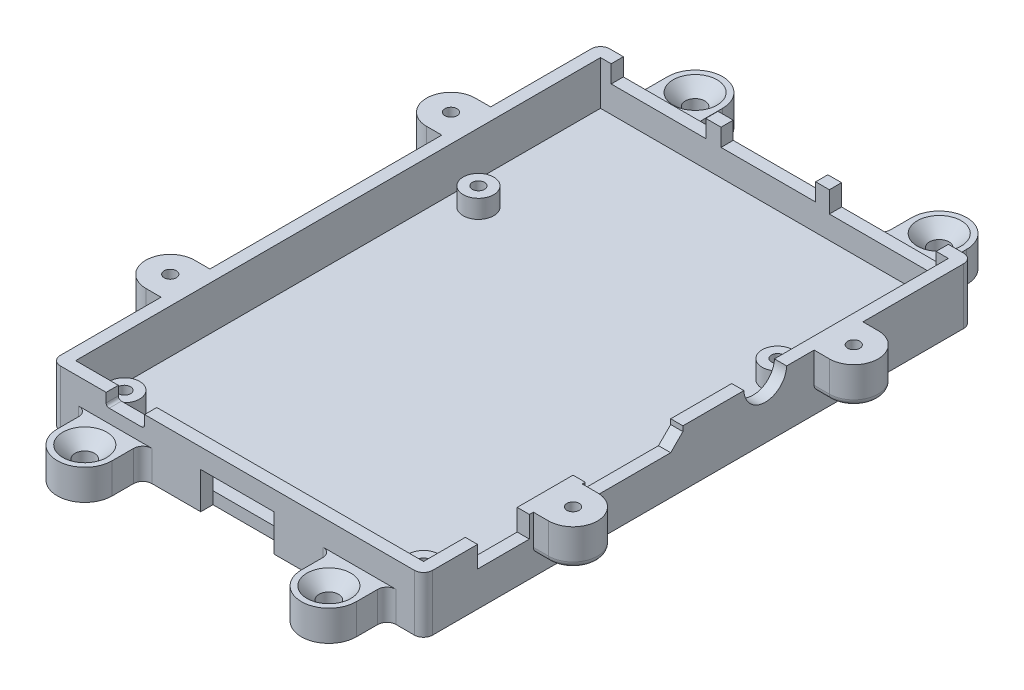
SolidWorks part; units mm, degrees
ref_plane "Спереди" through (0, 0, 0) normal (0, 0, 1) x (1, 0, 0)
ref_plane "Сверху" through (0, 0, 0) normal (0, 1, 0) x (1, 0, 0)
ref_plane "Справа" through (0, 0, 0) normal (1, 0, 0) x (0, 0, -1)
sketch "Эскиз1" plane through (0, 0, 0) normal (0, 1, 0) x (1, 0, 0)
  line L0 (0, 45) -> (0, -45) construction
  line L1 (-30.5, 45) -> (30.5, 45)
  line L2 (-30.5, 45) -> (-30.5, -45)
  line L3 (-30.5, -45) -> (30.5, -45)
  line L4 (30.5, 45) -> (30.5, -45)
  line L6 (-30.5, 0) -> (30.5, 0) construction
  point P8 (0, 0)
  dimension "D1" = 61
  dimension "D2" = 90
extrude "тело" add sketch "Эскиз1" along normal blind 9.2
sketch "Эскиз2" plane through (0, 9.2, 0) normal (0, 1, 0) x (1, 0, 0)
  line L0 (-28.5, -43) -> (28.5, 43) construction
  line L1 (-28.5, 43) -> (28.5, 43)
  line L2 (-28.5, 43) -> (-28.5, -43)
  line L3 (-28.5, -43) -> (28.5, -43)
  line L4 (28.5, 43) -> (28.5, -43)
  line L5 (0, 45) -> (0, -45) construction
  line L6 (30.5, 45) -> (-30.5, 45) construction
  line L7 (-30.5, -45) -> (30.5, -45) construction
  line L9 (-30.5, 45) -> (-30.5, -45) construction
  line L10 (-30.5, 0) -> (30.5, 0) construction
  line L11 (30.5, -45) -> (30.5, 45) construction
  point P16 (0, 0)
  dimension "D1" = 86
  dimension "D2" = 57
extrude "углубление под плату" cut sketch "Эскиз2" against normal blind 7.2
sketch "Эскиз3" plane through (0, 2, 0) normal (0, 1, 0) x (1, 0, 0)
  line L0 (0, 43) -> (0, -43) construction
  line L1 (-24.5, 19) -> (24.5, 19) construction
  line L2 (-24.5, 19) -> (-24.5, -39) construction
  line L3 (-24.5, -39) -> (24.5, -39) construction
  line L4 (24.5, 19) -> (24.5, -39) construction
  line L5 (28.5, 43) -> (-28.5, 43) construction
  line L6 (-28.5, -43) -> (28.5, -43) construction
  circle A0 centre (-24.5, 19) radius 2.5
  circle A1 centre (24.5, 19) radius 2.5
  circle A2 centre (24.5, -39) radius 2.5
  circle A3 centre (-24.5, -39) radius 2.5
  circle A4 centre (-24.5, 19) radius 1
  circle A5 centre (24.5, 19) radius 1
  circle A6 centre (24.5, -39) radius 1
  circle A7 centre (-24.5, -39) radius 1
  point P14 (0, -39)
  dimension "D4" = 5
  dimension "D5" = 2
  dimension "D1" = 49
  dimension "D2" = 58
  dimension "D3" = 4
extrude "стойки" add sketch "Эскиз3" along normal blind 3
sketch "Эскиз4" plane through (30.5, 0, 0) normal (1, 0, 0) x (0, 0, -1)
  line L0 (-45, 0) -> (45, 0) construction
  line L1 (-36.15, 9.7) -> (-27.65, 9.7)
  line L2 (-36.15, 9.7) -> (-36.15, 5.7)
  line L3 (-36.15, 5.7) -> (-27.65, 5.7)
  line L4 (-27.65, 9.7) -> (-27.65, 5.7)
  line L6 (-45, 9.2) -> (-45, 0) construction
  dimension "D1" = 8.5
  dimension "D2" = 4
  dimension "D3" = 5.7
  dimension "D4" = 8.85
extrude "отверстие под microusb" cut sketch "Эскиз4" against normal up to surface (2 mm away) up to face at (28.5, 5.6, 0)
sketch "Эскиз5" plane through (30.5, 0, 0) normal (1, 0, 0) x (0, 0, -1)
  line L0 (-45, 0) -> (45, 0) construction
  line L1 (-18.5, 12.43) -> (-2.5, 12.43)
  line L2 (-18.5, 12.43) -> (-18.5, 6.38)
  line L3 (-18.5, 6.38) -> (-2.5, 6.38)
  line L4 (-2.5, 12.43) -> (-2.5, 6.38)
  line L5 (-45, 9.2) -> (-45, 0) construction
  dimension "D1" = 16
  dimension "D2" = 6.05
  dimension "D3" = 6.38
  dimension "D4" = 26.5
extrude "отверстие под hdmi" cut sketch "Эскиз5" against normal up to surface (2 mm away) up to face at (28.5, 6.525, 15.95)
sketch "Эскиз6" plane through (30.5, 0, 0) normal (1, 0, 0) x (0, 0, -1)
  line L0 (-45, 9.2) -> (-45, 0) construction
  line L1 (-45, 0) -> (45, 0) construction
  circle A0 centre (11, 9.3) radius 3.5
  dimension "D1" = 7
  dimension "D2" = 56
  dimension "D3" = 9.3
extrude "отверстие под аудио" cut sketch "Эскиз6" against normal up to surface (2 mm away) up to face at (28.5, 6.9467, 14.1333)
sketch "Эскиз7" plane through (0, 0, -45) normal (0, 0, -1) x (-1, 0, 0)
  line L0 (-30.5, 9.2) -> (-30.5, 0) construction
  line L1 (-26.5, 19.75) -> (-9, 19.75)
  line L2 (-26.5, 19.75) -> (-26.5, 5.75)
  line L3 (-26.5, 5.75) -> (-9, 5.75)
  line L4 (-9, 19.75) -> (-9, 5.75)
  line L5 (-30.5, 0) -> (30.5, 0) construction
  dimension "D1" = 17.5
  dimension "D2" = 14
  dimension "D3" = 4
  dimension "D4" = 19.75
extrude "отверстие под ethernet" cut sketch "Эскиз7" against normal up to surface (2 mm away) up to face at (0, 5.6, -43)
sketch "Эскиз8" plane through (0, 0, -45) normal (0, 0, -1) x (-1, 0, 0)
  line L0 (-30.5, 9.2) -> (-30.5, 0) construction
  line L1 (-6.75, 22.45) -> (8.75, 22.45)
  line L2 (-6.75, 22.45) -> (-6.75, 6.33)
  line L3 (-6.75, 6.33) -> (8.75, 6.33)
  line L4 (8.75, 22.45) -> (8.75, 6.33)
  line L5 (-30.5, 0) -> (30.5, 0) construction
  dimension "D1" = 15.5
  dimension "D2" = 16.12
  dimension "D3" = 23.75
  dimension "D4" = 22.45
extrude "отверстие под usb" cut sketch "Эскиз8" against normal up to surface (2 mm away) up to face at (8.875, 6.5375, -43)
pattern_linear "Линейный массив1" count 2 spacing 18 along (-1, 0, 0) of "отверстие под usb"
sketch "Эскиз9" plane through (0, 0, 45) normal (0, 0, 1) x (1, 0, 0)
  line L1 (-6, 6) -> (6, 6)
  line L2 (-6, 6) -> (-6, 0)
  line L3 (-6, 0) -> (6, 0)
  line L4 (6, 6) -> (6, 0)
  point P4 (0, 0)
  dimension "D1" = 12
  dimension "D2" = 6
extrude "отверстие под microsd" cut sketch "Эскиз9" against normal up to surface (2 mm away) up to face at (0, 5.6, 43)
sketch "Эскиз10" plane through (0, 0, 0) normal (0, -1, 0) x (1, 0, 0)
  line L0 (-35, 44.5) -> (-30.5, 44.5) construction
  line L1 (-30.5, -45) -> (-30.5, 45) construction
  line L2 (-35, 35.5) -> (-30.5, 35.5) construction
  line L3 (-30.5, 44.5) -> (-30.5, 35.5) construction
  line L4 (0, 0) -> (0, 45) construction
  line L5 (6, 45) -> (-6, 45) construction
  line L6 (-30.5, 0) -> (30.5, 0) construction
  line L7 (30.5, 45) -> (30.5, -45) construction
  line L8 (-24.5, 50) -> (-24.5, 45)
  line L9 (-30.5, 45) -> (-6, 45) construction
  line L10 (-15.5, 50) -> (-15.5, 45)
  line L11 (-15.5, 45) -> (-24.5, 45)
  arc A0 (-35, 44.5) -> (-35, 35.5) centre (-35, 40) ccw construction
  circle A1 centre (-35, 40) radius 1.6 construction
  circle A2 centre (-20, 50) radius 1.6
  arc A3 (-15.5, 50) -> (-24.5, 50) centre (-20, 50) ccw
  dimension "D1" = 4.5
  dimension "D2" = 3.2
  dimension "D5" = 3.2
  dimension "D6" = 4.5
  dimension "D3" = 35
  dimension "D4" = 40
  dimension "D7" = 20
  dimension "D8" = 50
extrude "крепежное ухо" add sketch "Эскиз10" against normal blind 5
mirror "Зеркальное отражение1" about plane through (0, 0, 0) normal (1, 0, 0) of "крепежное ухо"
mirror "Зеркальное отражение2" about plane through (0, 0, 0) normal (0, 0, 1) of "Зеркальное отражение1", "крепежное ухо"
sketch "Эскиз11" plane through (0, 9.2, 0) normal (0, 1, 0) x (1, 0, 0)
  line L0 (-33, 27) -> (-30.5, 27)
  line L1 (-30.5, 45) -> (-30.5, -45) construction
  line L2 (-33, 19) -> (-30.5, 19)
  line L3 (-30.5, 19) -> (-30.5, 27)
  line L4 (0, -45) -> (0, 45) construction
  line L5 (-30.5, -45) -> (30.5, -45) construction
  line L6 (6.75, 45) -> (-8.75, 45) construction
  line L8 (-30.5, 0) -> (30.5, 0) construction
  line L9 (30.5, -2.5) -> (30.5, 7.5014) construction
  arc A0 (-33, 27) -> (-33, 19) centre (-33, 23) ccw
  circle A1 centre (-33, 23) radius 1
  dimension "D1" = 4
  dimension "D2" = 2
  dimension "D3" = 33
  dimension "D4" = 23
extrude "наплывы крепления крышки" add sketch "Эскиз11" against normal blind 6
mirror "Зеркальное отражение3" about plane through (0, 0, 0) normal (1, 0, 0) of "наплывы крепления крышки"
mirror "Зеркальное отражение4" about plane through (0, 0, 0) normal (0, 0, 1) of "Зеркальное отражение3", "наплывы крепления крышки"
chamfer "Фаска1" distance 2 angle 45 2 edges at (29.5, 6.38, 2.5) (29.5, 6.38, 18.5)
fillet "Скругление1" radius 1 12 edges at (-31.75, 3.2, 27) (-37, 3.2, 23) (-31.75, 3.2, 19) (-31.75, 3.2, -19) (-37, 3.2, -23) (-31.75, 3.2, -27) (31.75, 3.2, -19) (31.75, 3.2, -27) (37, 3.2, -23) (31.75, 3.2, 27) (31.75, 3.2, 19) (37, 3.2, 23)
fillet "Скругление2" radius 1.5 12 edges at (30.5, 4.6, -45) (-30.5, 4.6, -45) (-30.5, 4.6, 45) (30.5, 4.6, 45) (-24.5, 2.5, 45) (-15.5, 2.5, 45) (15.5, 2.5, 45) (24.5, 2.5, 45) (15.5, 2.5, -45) (24.5, 2.5, -45) (-15.5, 2.5, -45) (-24.5, 2.5, -45)
sketch "Эскиз12" plane through (0, 0, 45) normal (0, 0, 1) x (1, 0, 0)
  line L0 (-29, 9.2) -> (29, 9.2) construction
  line L1 (-21.5, 9.2) -> (-15.2, 9.2)
  line L2 (-21.5, 9.2) -> (-21.5, 7.2)
  line L3 (-21.5, 7.2) -> (-15.2, 7.2)
  line L4 (-15.2, 9.2) -> (-15.2, 7.2)
  line L5 (-30.5, 4.2) -> (-30.5, 9.2) construction
  dimension "D1" = 6.3
  dimension "D2" = 2
  dimension "D3" = 9
extrude "информационные светодиоды" cut sketch "Эскиз12" against normal up to surface (2 mm away) up to face at (0, 4.8, 43)
fillet "Скругление3" radius 0.5 2 edges at (-15.2, 7.2, 44) (-21.5, 7.2, 44)
chamfer "Фаска2" distance 2 angle 45 4 edges at (20, 5, -48.4) (-20, 5, -48.4) (20, 5, 48.4) (-20, 5, 48.4)
